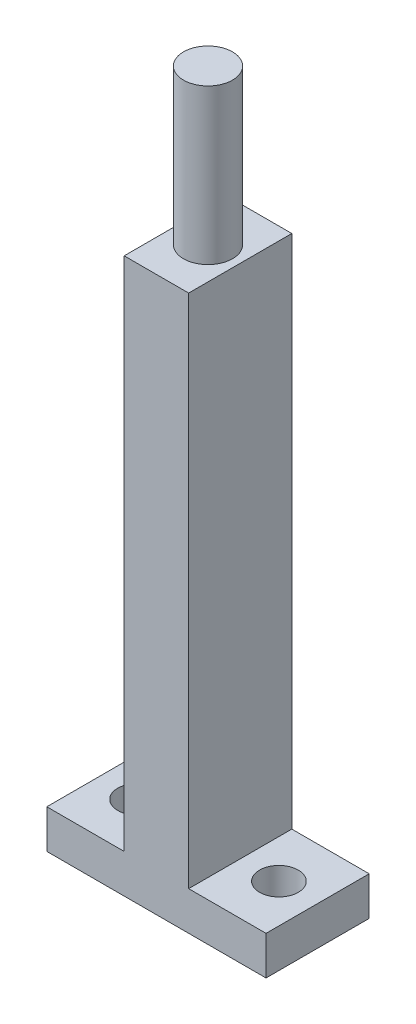
SolidWorks part; units mm, degrees
ref_plane "Front Plane" through (0, 0, 0) normal (0, 0, 1) x (1, 0, 0)
ref_plane "Top Plane" through (0, 0, 0) normal (0, 1, 0) x (1, 0, 0)
ref_plane "Right Plane" through (0, 0, 0) normal (1, 0, 0) x (0, 0, -1)
sketch "Sketch1" plane through (0, 0, 0) normal (0, 1, 0) x (1, 0, 0)
  circle A0 centre (0, 0) radius 1.9
  dimension "D1" = 3.8
extrude "Boss-Extrude1" add sketch "Sketch1" along normal blind 55
sketch "Sketch2" plane through (0, 0, 0) normal (0, -1, 0) x (1, 0, 0)
  line L1 (-8.5, -4) -> (8.5, -4)
  line L2 (-8.5, -4) -> (-8.5, 4)
  line L3 (-8.5, 4) -> (8.5, 4)
  line L4 (8.5, -4) -> (8.5, 4)
  line L5 (-8.5, -4) -> (8.5, 4) construction
  line L6 (-8.5, 4) -> (8.5, -4) construction
  point P0 (0, 0)
  dimension "D1" = 8
  dimension "D2" = 17
extrude "Boss-Extrude2" add sketch "Sketch2" against normal blind 3 contours L1 L4 L3 L2
sketch "Sketch3" plane through (0, 3, 0) normal (0, 1, 0) x (1, 0, 0)
  line L0 (0, 4) -> (0, -4) construction
  line L1 (-8.5, 4) -> (8.5, 4) construction
  line L2 (-8.5, -4) -> (8.5, -4) construction
  line L3 (-8.5, 0) -> (8.5, 0) construction
  line L4 (-8.5, 4) -> (-8.5, -4) construction
  line L5 (8.5, 4) -> (8.5, -4) construction
  circle A0 centre (-5.5, 0) radius 1.5
  circle A1 centre (5.5, 0) radius 1.5
  point P14 (-5.6697, 0)
  dimension "D1" = 3
  dimension "D2" = 3
extrude "Cut-Extrude1" cut sketch "Sketch3" against normal through all
sketch "Sketch4" plane through (0, 3, 0) normal (0, 1, 0) x (1, 0, 0)
  line L0 (-8.5, -4) -> (8.5, -4) construction
  line L1 (2.5, 4) -> (-2.5, 4)
  line L2 (2.5, 4) -> (2.5, -4)
  line L3 (2.5, -4) -> (-2.5, -4)
  line L4 (-2.5, 4) -> (-2.5, -4)
  line L5 (2.5, 4) -> (-2.5, -4) construction
  line L6 (2.5, -4) -> (-2.5, 4) construction
  point P0 (0, 0)
  dimension "D1" = 5
extrude "Boss-Extrude3" add sketch "Sketch4" along normal blind 40
